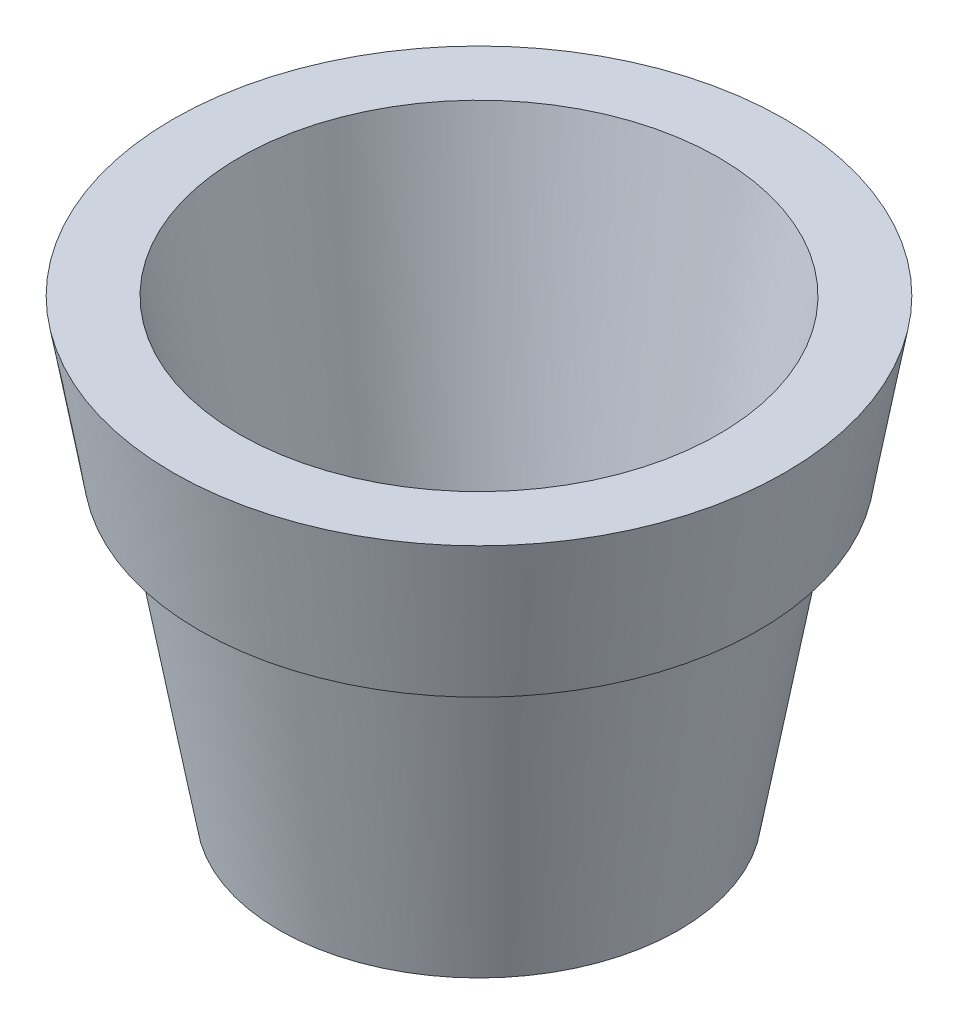
SolidWorks part; units mm, degrees
ref_plane "Front Plane" through (0, 0, 0) normal (0, 0, 1) x (1, 0, 0)
ref_plane "Top Plane" through (0, 0, 0) normal (0, 1, 0) x (1, 0, 0)
ref_plane "Right Plane" through (0, 0, 0) normal (1, 0, 0) x (0, 0, -1)
sketch "Sketch1" plane through (0, 0, 0) normal (0, 1, 0) x (1, 0, 0)
  circle A0 centre (0, 0) radius 20
extrude "Boss-Extrude1" add sketch "Sketch1" along normal blind 30 draft 10 draft outward yes
sketch "Sketch5" plane through (0, 30, 0) normal (0, 1, 0) x (1, 0, 0)
  circle A0 centre (0, 0) radius 28
extrude "Boss-Extrude3" add sketch "Sketch5" along normal blind 15 draft 10 draft outward yes
sketch "Sketch6" plane through (0, 45, 0) normal (0, 1, 0) x (1, 0, 0)
  circle A0 centre (0, 0) radius 24
extrude "Cut-Extrude3" cut sketch "Sketch6" against normal blind 40 draft 10
sketch "Sketch7" plane through (0, 5, 0) normal (0, 1, 0) x (1, 0, 0)
  circle A0 centre (0, 0) radius 4
extrude "Cut-Extrude4" cut sketch "Sketch7" against normal up to next
